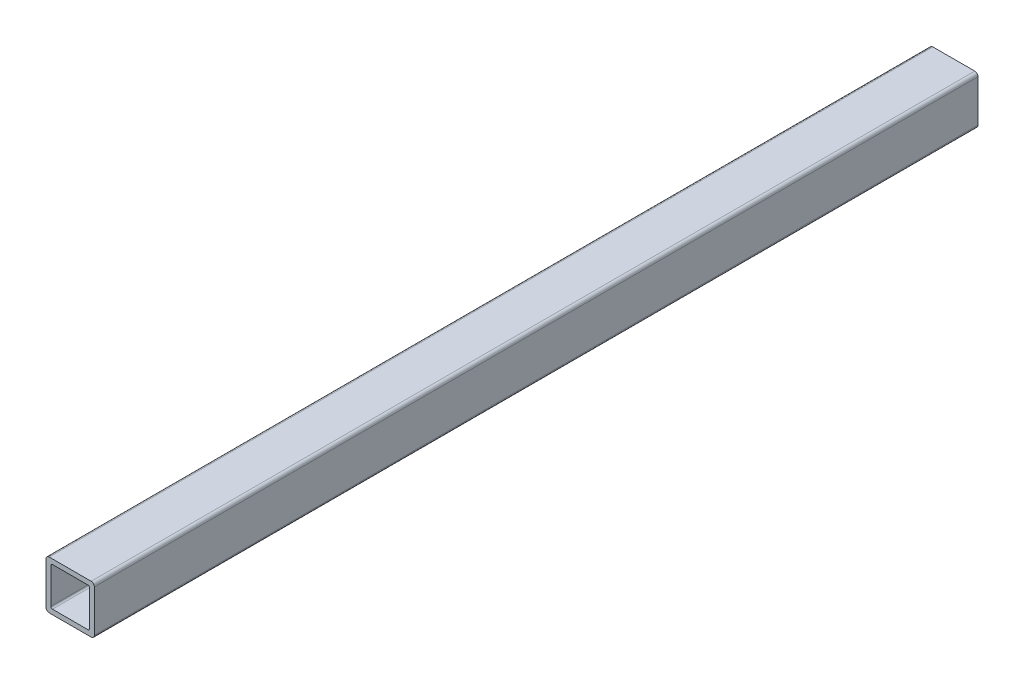
SolidWorks part; units mm, degrees
material "1.0553 (S355J0)"
ref_plane "Płaszczyzna przednia" through (0, 0, 0) normal (0, 0, 1) x (1, 0, 0)
ref_plane "Płaszczyzna górna" through (0, 0, 0) normal (0, 1, 0) x (1, 0, 0)
ref_plane "Płaszczyzna prawa" through (0, 0, 0) normal (1, 0, 0) x (0, 0, -1)
sketch "Szkic1" plane through (0, 0, 0) normal (0, 0, 1) x (1, 0, 0)
  line L1 (2, 0) -> (28, 0)
  line L2 (0, 2) -> (0, 28)
  line L3 (2, 30) -> (28, 30)
  line L4 (30, 2) -> (30, 28)
  line L5 (4, 3) -> (26, 3)
  line L6 (3, 4) -> (3, 26)
  line L7 (4, 27) -> (26, 27)
  line L8 (27, 4) -> (27, 26)
  arc A0 (0, 2) -> (2, 0) centre (2, 2) ccw
  arc A1 (28, 0) -> (30, 2) centre (28, 2) ccw
  arc A2 (30, 28) -> (28, 30) centre (28, 28) ccw
  arc A3 (2, 30) -> (0, 28) centre (2, 28) ccw
  arc A4 (3, 4) -> (4, 3) centre (4, 4) ccw
  arc A5 (26, 3) -> (27, 4) centre (26, 4) ccw
  arc A6 (27, 26) -> (26, 27) centre (26, 26) ccw
  arc A7 (4, 27) -> (3, 26) centre (4, 26) ccw
  point P7 (0, 0)
  point P12 (30, 30)
  point P15 (0, 30)
  dimension "D3" = 2
  dimension "D8" = 1
  dimension "D1" = 30
  dimension "D2" = 30
  dimension "D4" = 3
  dimension "D5" = 3
  dimension "D6" = 3
  dimension "D7" = 3
extrude "Dodanie-wyciągnięcie1" add sketch "Szkic1" along normal blind 548
